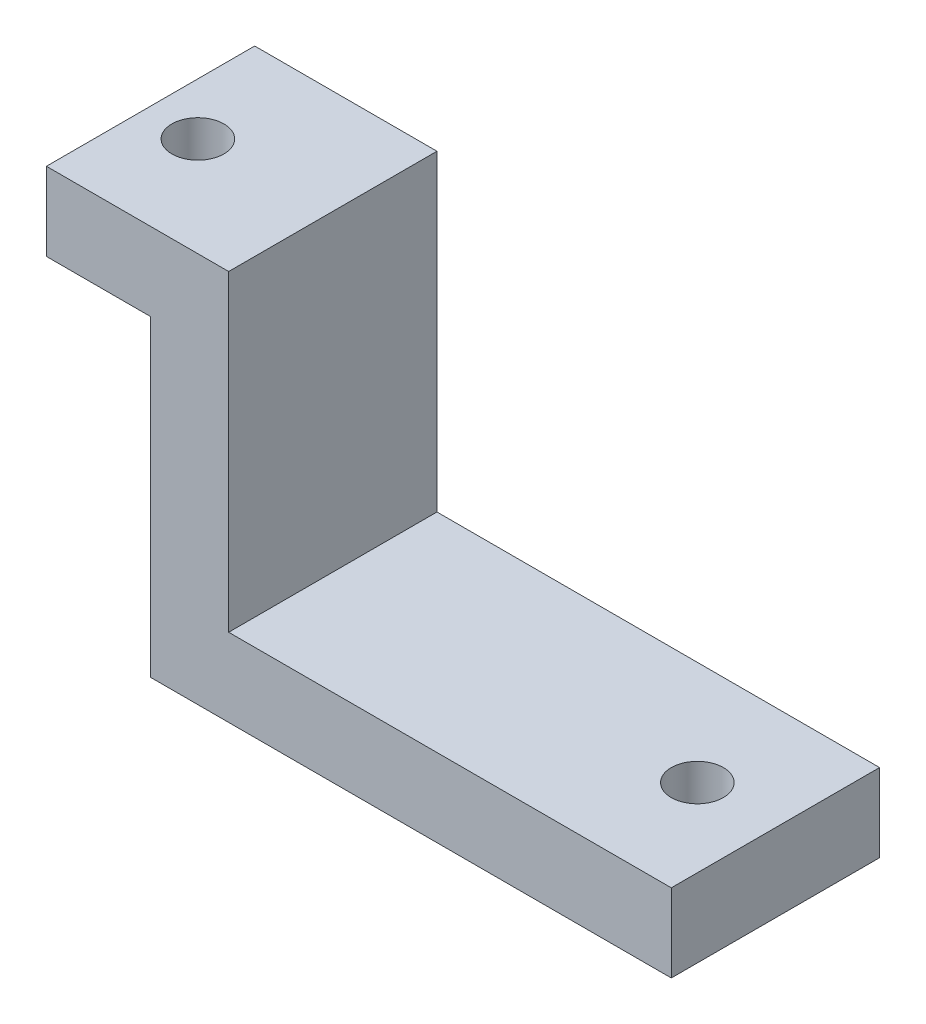
SolidWorks part; units mm, degrees
ref_plane "Front Plane" through (0, 0, 0) normal (0, 0, 1) x (1, 0, 0)
ref_plane "Top Plane" through (0, 0, 0) normal (0, 1, 0) x (1, 0, 0)
ref_plane "Right Plane" through (0, 0, 0) normal (1, 0, 0) x (0, 0, -1)
sketch "Sketch1" plane through (0, 0, 0) normal (1, 0, 0) x (0, 0, -1)
  line L0 (4, 15) -> (4, 0) construction
  line L1 (0, 0) -> (8, 0)
  line L2 (0, 0) -> (0, 15)
  line L3 (0, 15) -> (8, 15)
  line L4 (8, 0) -> (8, 15)
  line L5 (0, 7.5) -> (8, 7.5) construction
  dimension "D1" = 8
  dimension "D2" = 15
extrude "Boss-Extrude1" add sketch "Sketch1" along normal blind 3
sketch "Sketch2" plane through (0, 0, 0) normal (0, 1, 0) x (1, 0, 0)
  line L0 (20, 4) -> (3, 4) construction
  line L1 (3, 8) -> (20, 8)
  line L2 (3, 8) -> (3, 0)
  line L3 (3, 0) -> (20, 0)
  line L4 (20, 8) -> (20, 0)
  line L5 (11.5, 0) -> (11.5, 4) construction
  line L6 (11.5, 4) -> (11.5, 8) construction
  circle A0 centre (17, 4) radius 1
  dimension "D3" = 2
  dimension "D4" = 3
  dimension "D1" = 17
  dimension "D2" = 8
extrude "Boss-Extrude2" add sketch "Sketch2" along normal blind 3
sketch "Sketch3" plane through (0, 15, 0) normal (0, 1, 0) x (1, 0, 0)
  line L5 (0, 8) -> (-4, 8)
  line L6 (0, 8) -> (0, 0)
  line L7 (0, 0) -> (-4, 0)
  line L8 (-4, 8) -> (-4, 0)
  circle A0 centre (-2, 3.8177) radius 1
  dimension "D2" = 2
  dimension "D1" = 4
  dimension "D3" = 2
extrude "Boss-Extrude3" add sketch "Sketch3" against normal blind 3
